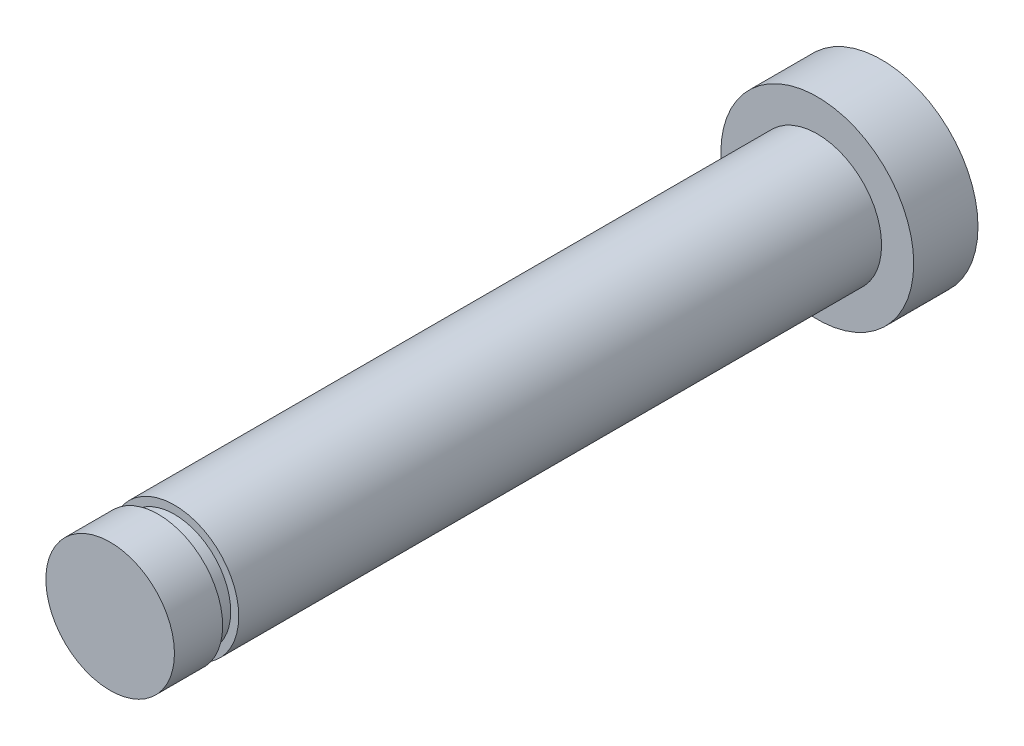
SolidWorks part; units mm, degrees
material "6061 合金"
ref_plane "前视基准面" through (0, 0, 0) normal (0, 0, 1) x (1, 0, 0)
ref_plane "上视基准面" through (0, 0, 0) normal (0, 1, 0) x (1, 0, 0)
ref_plane "右视基准面" through (0, 0, 0) normal (1, 0, 0) x (0, 0, -1)
sketch "草图1" plane through (0, 0, 0) normal (0, 0, 1) x (1, 0, 0)
  circle A0 centre (0, 0) radius 6
extrude "凸台-拉伸1" add sketch "草图1" along normal blind 4
sketch "草图2" plane through (0, 0, 4) normal (0, 0, 1) x (1, 0, 0)
  circle A0 centre (0, 0) radius 4
extrude "凸台-拉伸2" add sketch "草图2" along normal blind 40
sketch "草图3" plane through (0, 0, 44) normal (0, 0, 1) x (1, 0, 0)
  circle A0 centre (0, 0) radius 3.5
extrude "凸台-拉伸3" add sketch "草图3" along normal blind 1
sketch "草图4" plane through (0, 0, 45) normal (0, 0, 1) x (1, 0, 0)
  circle A0 centre (0, 0) radius 4
extrude "凸台-拉伸4" add sketch "草图4" along normal blind 3
